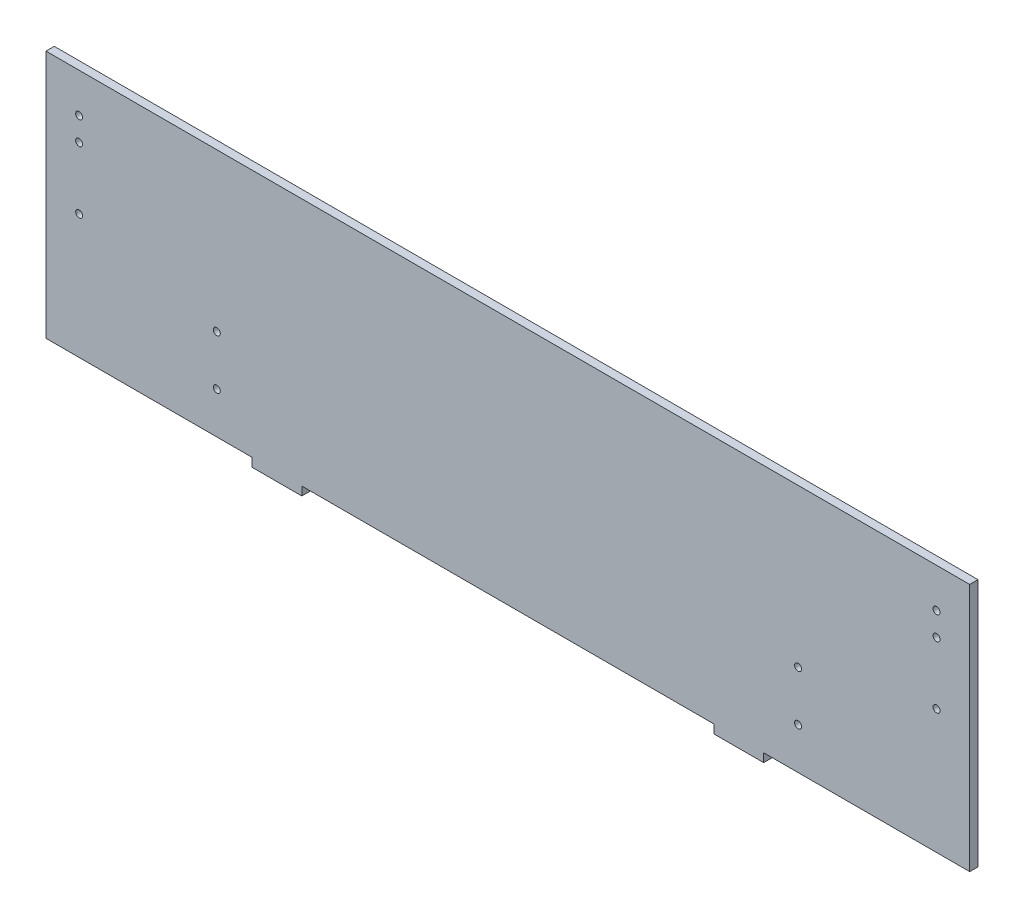
SolidWorks part; units mm, degrees
ref_plane "Front Plane" through (0, 0, 0) normal (0, 0, 1) x (1, 0, 0)
ref_plane "Top Plane" through (0, 0, 0) normal (0, 1, 0) x (1, 0, 0)
ref_plane "Right Plane" through (0, 0, 0) normal (1, 0, 0) x (0, 0, -1)
sketch "Sketch1" plane through (0, 0, 0) normal (0, 0, 1) x (1, 0, 0)
  line L1 (-296.0125, -5.0752) -> (260.9875, -5.0752)
  line L2 (-296.0125, -5.0752) -> (-296.0125, -155.0752)
  line L3 (-296.0125, -155.0752) -> (260.9875, -155.0752)
  line L4 (260.9875, -5.0752) -> (260.9875, -155.0752)
  dimension "D1" = 557
  dimension "D2" = 150
extrude "Boss-Extrude1" add sketch "Sketch1" along normal blind 5
sketch "Sketch2" plane through (0, 0, 5) normal (0, 0, 1) x (1, 0, 0)
  line L0 (-17.5125, -155.0752) -> (260.9875, -155.0752) construction
  line L1 (-296.0125, -155.0752) -> (260.9875, -155.0752) construction
  line L2 (-17.5125, -155.0752) -> (-296.0125, -155.0752) construction
  line L4 (-171.7625, -149.8752) -> (-141.7625, -149.8752)
  line L5 (-171.7625, -149.8752) -> (-171.7625, -160.2752)
  line L6 (-171.7625, -160.2752) -> (-141.7625, -160.2752)
  line L7 (-141.7625, -149.8752) -> (-141.7625, -160.2752)
  line L8 (-171.7625, -149.8752) -> (-141.7625, -160.2752) construction
  line L9 (-171.7625, -160.2752) -> (-141.7625, -149.8752) construction
  line L10 (106.7375, -149.8752) -> (136.7375, -149.8752)
  line L11 (106.7375, -149.8752) -> (106.7375, -160.2752)
  line L12 (106.7375, -160.2752) -> (136.7375, -160.2752)
  line L13 (136.7375, -149.8752) -> (136.7375, -160.2752)
  line L14 (106.7375, -149.8752) -> (136.7375, -160.2752) construction
  line L15 (106.7375, -160.2752) -> (136.7375, -149.8752) construction
  point P5 (-156.7625, -155.0752)
  point P12 (121.7375, -155.0752)
  dimension "D1" = 30
  dimension "D2" = 10.4
  dimension "D3" = 10.4
  dimension "D4" = 30
extrude "Boss-Extrude2" add sketch "Sketch2" against normal blind 5
sketch "Sketch3" plane through (0, 0, 5) normal (0, 0, 1) x (1, 0, 0)
  line L0 (260.9875, -5.0752) -> (-296.0125, -5.0752) construction
  line L2 (-296.0125, -5.0752) -> (-296.0125, -155.0752) construction
  line L3 (-17.5125, -5.0752) -> (-17.5125, -155.0752) construction
  line L4 (-141.7625, -155.0752) -> (106.7375, -155.0752) construction
  circle A0 centre (-276.0125, -28.7052) radius 2.1
  circle A1 centre (-276.0125, -42.7752) radius 2.1
  circle A2 centre (240.9875, -42.7752) radius 2.1
  circle A3 centre (240.9875, -28.7052) radius 2.1
  dimension "D1" = 4.2
  dimension "D2" = 4.2
  dimension "D3" = 23.63
  dimension "D4" = 20
  dimension "D5" = 20
  dimension "D6" = 37.7
extrude "Cut-Extrude1" cut sketch "Sketch3" against normal blind 10
sketch "Sketch4" plane through (0, 0, 0) normal (0, 0, -1) x (-1, 0, 0)
  line L0 (-260.9875, -155.0752) -> (-260.9875, -5.0752) construction
  line L1 (296.0125, -5.0752) -> (296.0125, -155.0752) construction
  circle A0 centre (-240.9875, -80.0752) radius 2.1
  circle A1 centre (276.0125, -80.0752) radius 2.1
  dimension "D2" = 4.2
  dimension "D4" = 4.2
  dimension "D1" = 20
  dimension "D3" = 20
extrude "Cut-Extrude2" cut sketch "Sketch4" against normal blind 10
sketch "Sketch5" plane through (0, 0, 0) normal (0, 0, -1) x (-1, 0, 0)
  line L0 (-136.7375, -155.0752) -> (-106.7375, -155.0752) construction
  line L1 (-260.9875, -155.0752) -> (-260.9875, -5.0752) construction
  circle A0 centre (-157.4875, -130.0752) radius 2.1
  circle A1 centre (-157.4875, -100.0752) radius 2.1
  dimension "D1" = 4.2
  dimension "D3" = 4.2
  dimension "D2" = 25
  dimension "D4" = 30
  dimension "D5" = 103.5
extrude "Cut-Extrude3" cut sketch "Sketch5" against normal blind 10
sketch "Sketch6" plane through (0, 0, 0) normal (0, 0, -1) x (-1, 0, 0)
  line L0 (141.7625, -155.0752) -> (171.7625, -155.0752) construction
  line L1 (296.0125, -5.0752) -> (296.0125, -155.0752) construction
  circle A0 centre (193.0125, -130.0752) radius 2.1
  circle A1 centre (193.0125, -100.0752) radius 2.1
  dimension "D1" = 4.2
  dimension "D2" = 4.2
  dimension "D3" = 25
  dimension "D4" = 30
  dimension "D5" = 103
extrude "Cut-Extrude4" cut sketch "Sketch6" against normal blind 10
